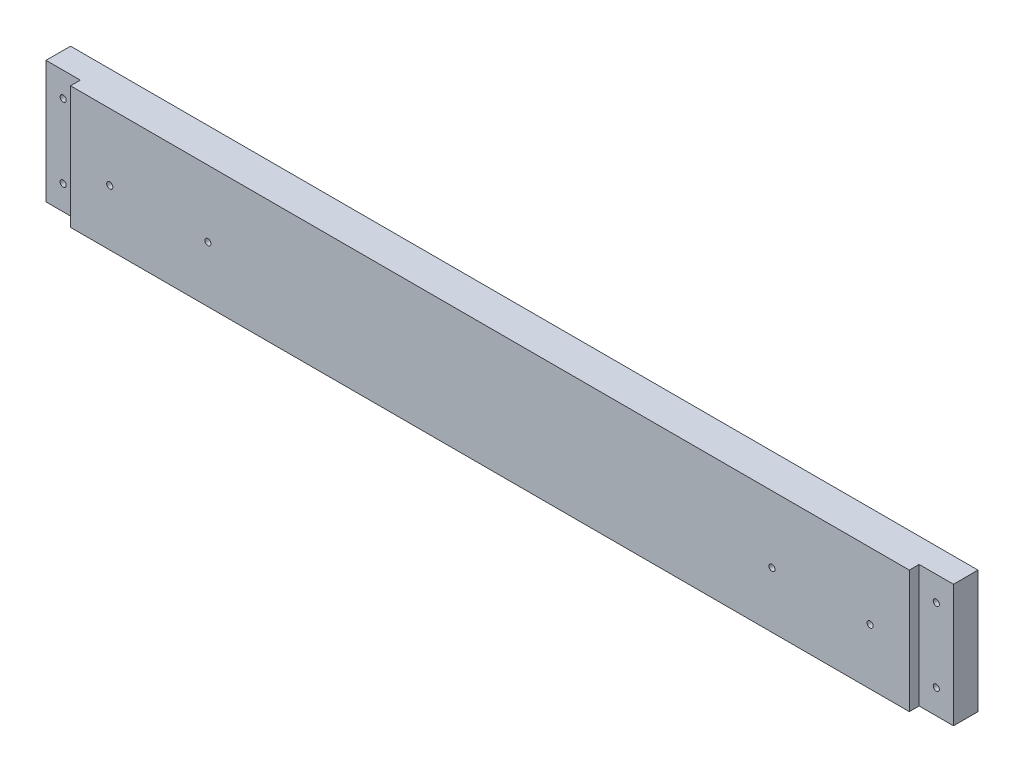
SolidWorks part; units mm, degrees
material "Pine"
ref_plane "Front Plane" through (0, 0, 0) normal (0, 0, 1) x (1, 0, 0)
ref_plane "Top Plane" through (0, 0, 0) normal (0, 1, 0) x (1, 0, 0)
ref_plane "Right Plane" through (0, 0, 0) normal (1, 0, 0) x (0, 0, -1)
sketch "Sketch1" plane through (0, 0, 0) normal (0, 0, 1) x (1, 0, 0)
  line L0 (8932.6508, -5243.5125) -> (10226.1458, -5243.5125)
  line L1 (9086.3208, -4722.0918) -> (10222.9708, -4853.7812)
  line L2 (8914.8708, -6342.0625) -> (10197.5708, -6342.0625)
  line L3 (8914.8708, -5808.6625) -> (10197.5708, -5808.6625)
  line L4 (8919.6333, -5253.0375) -> (10218.2083, -5253.0375)
  line L5 (9134.2633, -4656.1375) -> (9134.2633, -4638.3575)
  line L6 (9091.0833, -4638.3575) -> (9134.2633, -4638.3575)
  line L7 (9091.0833, -4567.2375) -> (9091.0833, -4638.3575)
  line L8 (9134.2633, -4656.1375) -> (9581.3033, -4656.1375)
  line L9 (9091.0833, -4567.2375) -> (9624.4833, -4567.2375)
  line L10 (9581.3033, -4656.1375) -> (9581.3033, -4638.3575)
  line L11 (9581.3033, -4638.3575) -> (9624.4833, -4638.3575)
  line L12 (9624.4833, -4567.2375) -> (9624.4833, -4638.3575)
  line L13 (8932.6508, -5225.7325) -> (9344.9775, -5225.7325)
  line L14 (8932.6508, -5256.2125) -> (8932.6508, -5243.5125)
  line L15 (8911.6958, -5256.2125) -> (8932.6508, -5256.2125)
  line L16 (8914.8708, -4722.0918) -> (9086.3208, -4722.0918)
  line L17 (8911.6958, -4715.5913) -> (8932.6508, -4715.5913)
  line L18 (8914.8708, -6342.0625) -> (8914.8708, -5808.6625)
  line L19 (12082.9917, -4722.0918) -> (10946.3417, -4853.7812)
  line L20 (12236.6617, -5243.5125) -> (10943.1667, -5243.5125)
  line L21 (10951.1042, -5253.0375) -> (12249.6792, -5253.0375)
  line L22 (10838.3917, -5656.2625) -> (11308.2917, -5656.2625)
  line L23 (10838.3917, -5719.7625) -> (11308.2917, -5719.7625)
  line L24 (10838.3917, -5742.5368) -> (11308.2917, -5742.5368)
  line L25 (10806.6417, -6342.0625) -> (11340.0417, -6342.0625)
  line L26 (10803.4667, -6335.7125) -> (11343.2167, -6335.7125)
  line L27 (10803.4667, -6317.9325) -> (11343.2167, -6317.9325)
  line L28 (10943.1667, -5225.7325) -> (11376.4483, -5225.7325)
  line L29 (11506.7292, -4754.5625) -> (10806.6417, -4827.5875)
  line L30 (11506.7292, -4567.2375) -> (11506.7292, -4754.5625)
  line L31 (10806.6417, -4567.2375) -> (10806.6417, -4827.5875)
  line L32 (10806.6417, -4567.2375) -> (11506.7292, -4567.2375)
  line L33 (10235.6708, -6329.3625) -> (10245.1958, -6329.3625)
  line L34 (10245.1958, -6329.3625) -> (10254.7208, -6278.5625)
  line L35 (10302.3458, -6329.3625) -> (10311.8708, -6278.5625)
  line L36 (10302.3458, -6329.3625) -> (10292.8208, -6329.3625)
  line L37 (10245.1958, -5821.3625) -> (10254.7208, -5872.1625)
  line L38 (10235.6708, -5821.3625) -> (10245.1958, -5821.3625)
  line L39 (10292.8208, -5821.3625) -> (10302.3458, -5821.3625)
  line L40 (10302.3458, -5821.3625) -> (10311.8708, -5872.1625)
  line L41 (10235.6708, -5821.3625) -> (10235.6708, -6329.3625)
  line L42 (10254.7208, -5872.1625) -> (10254.7208, -6278.5625)
  line L43 (10311.8708, -5872.1625) -> (10311.8708, -6278.5625)
  line L44 (10292.8208, -5821.3625) -> (10292.8208, -6329.3625)
  line L45 (8932.6508, -5225.7325) -> (8932.6508, -4715.5913)
  line L46 (8911.6958, -4715.5913) -> (8911.6958, -5256.2125)
  line L47 (8914.8708, -5248.275) -> (8914.8708, -4722.0918)
  line L48 (8919.6333, -5253.0375) -> (8914.8708, -5248.275)
  line L49 (8914.8708, -5145.0875) -> (8937.426, -5145.0875)
  line L50 (8914.8708, -5202.2375) -> (8937.426, -5202.2375)
  line L51 (10838.3917, -5656.2625) -> (10838.3917, -5719.7625)
  line L52 (10832.0417, -5736.1868) -> (10856.1717, -5736.1868)
  line L53 (10806.6417, -6342.0625) -> (10806.6417, -5818.7368)
  line L54 (10832.0417, -5649.9125) -> (10856.1717, -5649.9125)
  line L55 (10832.0417, -5726.1125) -> (10856.1717, -5726.1125)
  line L56 (10806.6417, -5818.7368) -> (10833.9015, -5818.7368)
  line L57 (10832.0417, -5806.0442) -> (10851.6815, -5806.0442)
  line L58 (10856.1717, -5801.5541) -> (10856.1717, -5736.1868)
  line L59 (10838.3917, -5814.2467) -> (10838.3917, -5742.5368)
  line L60 (10832.0417, -5806.0442) -> (10832.0417, -5736.1868)
  line L61 (10803.4667, -6317.9325) -> (10803.4667, -6335.7125)
  line L62 (10197.5708, -5808.6625) -> (10197.5708, -6342.0625)
  line L63 (9762.3842, -6348.4125) -> (9762.3842, -5802.3125)
  line L64 (9780.1642, -6348.4125) -> (9762.3842, -6348.4125)
  line L65 (9780.1642, -5802.3125) -> (9780.1642, -6348.4125)
  line L66 (9762.3842, -5802.3125) -> (9780.1642, -5802.3125)
  line L67 (9332.2775, -6348.4125) -> (9332.2775, -5802.3125)
  line L68 (9332.2775, -6348.4125) -> (9350.0575, -6348.4125)
  line L69 (9350.0575, -5802.3125) -> (9350.0575, -6348.4125)
  line L70 (9332.2775, -5802.3125) -> (9350.0575, -5802.3125)
  line L71 (9993.8374, -6061.075) -> (9993.8374, -6045.2418)
  line L72 (9998.5999, -6065.8375) -> (10014.4331, -6065.8375)
  line L73 (9998.5999, -6084.8875) -> (10014.4331, -6084.8875)
  line L74 (9993.8374, -6105.4832) -> (9993.8374, -6089.65)
  line L75 (9974.7874, -6105.4832) -> (9974.7874, -6089.65)
  line L76 (9954.1917, -6084.8875) -> (9970.0249, -6084.8875)
  line L77 (9974.7874, -6061.075) -> (9974.7874, -6045.2418)
  line L78 (9954.1917, -6065.8375) -> (9970.0249, -6065.8375)
  line L79 (10793.9417, -6237.2875) -> (10816.4969, -6237.2875)
  line L80 (10793.9417, -6294.4375) -> (10816.4969, -6294.4375)
  line L81 (10856.1717, -5649.9125) -> (10856.1717, -5726.1125)
  line L82 (10832.0417, -5726.1125) -> (10832.0417, -5649.9125)
  line L83 (10226.1458, -5225.7325) -> (10226.1458, -5243.5125)
  line L84 (10205.1908, -5257.8) -> (10205.1908, -4844.2499)
  line L85 (10230.9083, -4844.2499) -> (10230.9083, -5257.8)
  line L86 (10205.1908, -5257.8) -> (10230.9083, -5257.8)
  line L87 (10205.1908, -4844.2499) -> (10230.9083, -4844.2499)
  line L88 (10946.3417, -5176.8375) -> (10968.8969, -5176.8375)
  line L89 (9349.4676, -5141.9125) -> (9358.2674, -5141.9125)
  line L90 (10946.3417, -5119.6875) -> (10968.8969, -5119.6875)
  line L91 (9929.011, -4660.9635) -> (10066.0807, -4660.9635)
  line L92 (9929.011, -4678.7435) -> (10066.0807, -4678.7435)
  line L93 (10943.1667, -5225.7325) -> (10943.1667, -5243.5125)
  line L94 (10946.3417, -5248.275) -> (10951.1042, -5253.0375)
  line L95 (10946.3417, -5257.8063) -> (10946.3417, -4849.0188)
  line L96 (10964.1217, -5257.8) -> (10964.1217, -4844.2499)
  line L97 (10938.4042, -4844.2499) -> (10938.4042, -5257.8)
  line L98 (10938.4042, -5257.8) -> (10964.1217, -5257.8)
  line L99 (10964.1217, -4844.2499) -> (10938.4042, -4844.2499)
  line L100 (10344.8908, -4560.8875) -> (10369.0208, -4560.8875)
  line L101 (10344.8908, -4560.8875) -> (10369.0208, -4560.8875)
  line L102 (10800.2917, -4560.8875) -> (10824.4217, -4560.8875)
  line L103 (10200.4156, -5119.6875) -> (10222.9708, -5119.6875)
  line L104 (10200.4156, -5176.8375) -> (10222.9708, -5176.8375)
  line L105 (9344.9775, -5146.4026) -> (9344.9775, -5225.7325)
  line L106 (10344.8908, -4560.8875) -> (10344.8908, -4833.9375)
  line L107 (9792.8642, -5225.7325) -> (9792.8642, -5146.4026)
  line L108 (9362.7575, -5225.7325) -> (9775.0842, -5225.7325)
  line L109 (9680.3633, -4761.8396) -> (9680.3633, -4559.9604)
  line L110 (9656.2333, -4559.9604) -> (9680.3633, -4559.9604)
  line L111 (9656.2333, -4761.8396) -> (9680.3633, -4761.8396)
  line L112 (9656.2333, -4761.8396) -> (9656.2333, -4559.9604)
  line L113 (9779.5743, -5141.9125) -> (9788.374, -5141.9125)
  line L114 (10070.5708, -4665.4536) -> (10070.5708, -4674.2534)
  line L115 (9924.5208, -4674.2534) -> (9924.5208, -4665.4536)
  line L116 (12127.4417, -6188.3925) -> (12205.5015, -6188.3925)
  line L117 (12209.9917, -6170.6125) -> (12209.9917, -6183.9024)
  line L118 (9792.8642, -5225.7325) -> (10226.1458, -5225.7325)
  line L119 (9662.5833, -4754.5625) -> (10362.6708, -4827.5875)
  line L120 (9662.5833, -4567.2375) -> (9662.5833, -4754.5625)
  line L121 (10362.6708, -4567.2375) -> (10362.6708, -4827.5875)
  line L122 (9662.5833, -4567.2375) -> (10362.6708, -4567.2375)
  line L123 (10824.4217, -4833.9375) -> (10800.2917, -4833.9375)
  line L124 (10800.2917, -4833.9375) -> (10800.2917, -4560.8875)
  line L125 (10824.4217, -4560.8875) -> (10824.4217, -4833.9375)
  line L126 (10344.8908, -4833.9375) -> (10369.0208, -4833.9375)
  line L127 (10369.0208, -4833.9375) -> (10369.0208, -4560.8875)
  line L128 (10222.9708, -5248.275) -> (10218.2083, -5253.0375)
  line L129 (10222.9708, -5257.8063) -> (10222.9708, -4849.0188)
  line L130 (11734.6544, -5701.375) -> (11739.2301, -5701.375)
  line L131 (9362.7575, -5225.7325) -> (9362.7575, -5146.4026)
  line L132 (9775.0842, -5146.4026) -> (9775.0842, -5225.7325)
  line L133 (11761.3864, -5701.375) -> (11756.8282, -5701.375)
  line L134 (11734.6544, -5693.755) -> (11739.2301, -5693.755)
  line L135 (11761.4039, -5693.755) -> (11756.8282, -5693.755)
  line L136 (11734.6544, -5701.375) -> (11739.2301, -5701.375)
  line L137 (11744.3462, -5721.3024) -> (11744.3462, -5706.4179)
  line L138 (11751.7122, -5721.3024) -> (11751.7122, -5706.4179)
  line L139 (11740.0917, -6170.6125) -> (11740.0917, -6183.9024)
  line L140 (11689.2917, -6188.3925) -> (11822.6417, -6188.3925)
  line L141 (11689.2917, -6348.4093) -> (11689.2917, -6164.2657)
  line L142 (11689.2917, -6164.2657) -> (11746.4417, -6164.2657)
  line L143 (11746.4417, -6164.2657) -> (11746.4417, -6188.3925)
  line L144 (11689.2917, -6164.2657) -> (11746.4417, -6164.2657)
  line L145 (11340.0417, -5818.7368) -> (11340.0417, -6342.0625)
  line L146 (11290.5117, -5726.1125) -> (11314.6417, -5726.1125)
  line L147 (11290.5117, -5649.9125) -> (11290.5117, -5726.1125)
  line L148 (11340.0417, -5818.7368) -> (11312.7818, -5818.7368)
  line L149 (11314.6417, -5806.0442) -> (11295.0018, -5806.0442)
  line L150 (11290.5117, -5801.5541) -> (11290.5117, -5736.1868)
  line L151 (11308.2917, -5814.2467) -> (11308.2917, -5742.5368)
  line L152 (11314.6417, -5806.0442) -> (11314.6417, -5736.1868)
  line L153 (11290.5117, -5736.1868) -> (11314.6417, -5736.1868)
  line L154 (11848.0417, -6267.1325) -> (11962.3417, -6267.1325)
  line L155 (11962.3417, -6267.1325) -> (11962.3417, -6203.6325)
  line L156 (11343.2167, -6317.9325) -> (11343.2167, -6335.7125)
  line L157 (11365.4417, -5656.2625) -> (11365.4417, -5719.7625)
  line L158 (11365.4417, -5656.2625) -> (11479.7417, -5656.2625)
  line L159 (11778.1917, -6071.3937) -> (11802.3217, -6071.3937)
  line L160 (11314.6417, -5726.1125) -> (11314.6417, -5649.9125)
  line L161 (11314.6417, -5649.9125) -> (11290.5117, -5649.9125)
  line L162 (11308.2917, -5719.7625) -> (11308.2917, -5656.2625)
  line L163 (11689.2917, -6348.4093) -> (11713.4217, -6348.4093)
  line L164 (12203.6417, -6164.2657) -> (12260.7917, -6164.2657)
  line L165 (11713.4217, -6348.4093) -> (11713.4217, -6164.2657)
  line L166 (11695.6417, -6342.0625) -> (11695.6417, -6170.6125)
  line L167 (11695.6417, -6048.5337) -> (11699.4517, -6052.3437)
  line L168 (11822.6417, -6292.5325) -> (11822.6417, -6188.3925)
  line L169 (11695.6417, -6342.0625) -> (11695.6417, -6170.6125)
  line L170 (11848.0417, -6203.6325) -> (11962.3417, -6203.6325)
  line L171 (11848.0417, -6203.6325) -> (11848.0417, -6267.1325)
  line L172 (11987.7417, -6267.1325) -> (11987.7417, -6203.6325)
  line L173 (11784.5417, -6077.7437) -> (11784.5417, -6141.2438)
  line L174 (11517.8417, -5656.2625) -> (11632.1417, -5656.2625)
  line L175 (11632.1417, -5656.2625) -> (11632.1417, -5719.7625)
  line L176 (11632.1417, -5719.7625) -> (11517.8417, -5719.7625)
  line L177 (11517.8417, -5719.7625) -> (11517.8417, -5656.2625)
  line L178 (11692.4667, -6028.2137) -> (11692.4667, -6045.9937)
  line L179 (11695.6417, -5979.3188) -> (11718.1969, -5979.3188)
  line L180 (11695.6417, -5922.1687) -> (11718.1969, -5922.1687)
  line L181 (11821.0415, -5722.9375) -> (11821.0415, -5943.6)
  line L182 (11687.7042, -5651.5) -> (11701.9917, -5651.5)
  line L183 (11687.7042, -5651.5) -> (11687.7042, -6055.5251)
  line L184 (11687.7042, -6055.5251) -> (11701.9917, -6055.5251)
  line L185 (11701.9917, -6055.5251) -> (11701.9917, -5651.5)
  line L186 (11695.6417, -6055.2013) -> (11695.6417, -5649.595)
  line L187 (11695.6417, -5656.2625) -> (11695.6417, -6048.5337)
  line L188 (11695.6417, -6170.6125) -> (11740.0917, -6170.6125)
  line L189 (12203.6417, -6164.2657) -> (12203.6417, -6188.3925)
  line L190 (12254.4417, -6342.0625) -> (12254.4417, -6170.6125)
  line L191 (12129.0419, -5943.6) -> (12129.0419, -5722.9375)
  line L192 (12254.4417, -6048.5337) -> (12250.6317, -6052.3437)
  line L193 (12257.6167, -6045.9937) -> (12257.6167, -6028.2137)
  line L194 (12248.0917, -5651.5) -> (12262.3792, -5651.5)
  line L195 (12262.3792, -5651.5) -> (12262.3792, -6055.5251)
  line L196 (12262.3792, -6055.5251) -> (12248.0917, -6055.5251)
  line L197 (12248.0917, -6055.5251) -> (12248.0917, -5651.5)
  line L198 (12254.4417, -6141.2438) -> (12254.4417, -6077.7437)
  line L199 (12236.6617, -6164.2657) -> (12260.7917, -6164.2657)
  line L200 (12102.0417, -6267.1325) -> (11987.7417, -6267.1325)
  line L201 (11330.1865, -6237.2875) -> (11352.7417, -6237.2875)
  line L202 (11330.1865, -6294.4375) -> (11352.7417, -6294.4375)
  line L203 (11474.6617, -5851.8425) -> (11492.4417, -5851.8425)
  line L204 (11474.6617, -5808.6625) -> (11474.6617, -5851.8425)
  line L205 (11403.5417, -5808.6625) -> (11474.6617, -5808.6625)
  line L206 (11492.4417, -5851.8425) -> (11492.4417, -6298.8825)
  line L207 (11403.5417, -6342.0625) -> (11403.5417, -5808.6625)
  line L208 (11474.6617, -6298.8825) -> (11492.4417, -6298.8825)
  line L209 (11474.6617, -6342.0625) -> (11474.6617, -6298.8825)
  line L210 (11403.5417, -6342.0625) -> (11474.6617, -6342.0625)
  line L211 (11619.4417, -5851.8425) -> (11601.6617, -5851.8425)
  line L212 (11601.6617, -5808.6625) -> (11601.6617, -5851.8425)
  line L213 (11530.5417, -5808.6625) -> (11601.6617, -5808.6625)
  line L214 (11619.4417, -5851.8425) -> (11619.4417, -6298.8825)
  line L215 (11530.5417, -6342.0625) -> (11530.5417, -5808.6625)
  line L216 (11619.4417, -6298.8825) -> (11601.6617, -6298.8825)
  line L217 (11601.6617, -6342.0625) -> (11601.6617, -6298.8825)
  line L218 (11530.5417, -6342.0625) -> (11601.6617, -6342.0625)
  line L219 (11479.7417, -5719.7625) -> (11479.7417, -5656.2625)
  line L220 (11365.4417, -5719.7625) -> (11479.7417, -5719.7625)
  line L221 (11778.1917, -6147.5937) -> (11802.3217, -6147.5937)
  line L222 (11802.3217, -6071.3937) -> (11802.3217, -6147.5937)
  line L223 (11778.1917, -6147.5937) -> (11778.1917, -6071.3937)
  line L224 (12254.4417, -5922.1687) -> (12231.8865, -5922.1687)
  line L225 (12254.4417, -5979.3188) -> (12231.8865, -5979.3188)
  line L226 (12254.4417, -6055.2013) -> (12254.4417, -5649.595)
  line L227 (12254.4417, -6048.5337) -> (12254.4417, -5656.2625)
  line L228 (11841.6917, -5702.2873) -> (12108.3917, -5702.2873)
  line L229 (11822.6417, -6292.5325) -> (12127.4417, -6292.5325)
  line L230 (12127.4417, -6292.5325) -> (12127.4417, -6188.3925)
  line L231 (12254.4417, -6170.6125) -> (12209.9917, -6170.6125)
  line L232 (11695.6417, -6342.0625) -> (12254.4417, -6342.0625)
  line L233 (12236.6617, -6348.4093) -> (12260.7917, -6348.4093)
  line L234 (12260.7917, -6348.4093) -> (12260.7917, -6164.2657)
  line L235 (12236.6617, -6348.4093) -> (12236.6617, -6164.2657)
  line L236 (12102.0417, -6203.6325) -> (12102.0417, -6267.1325)
  line L237 (11987.7417, -6203.6325) -> (12102.0417, -6203.6325)
  line L238 (12236.6617, -6147.5937) -> (12236.6617, -6071.3937)
  line L239 (12203.6417, -6188.3925) -> (12260.7917, -6188.3925)
  line L240 (11098.7417, -4665.4536) -> (11098.7417, -4674.2534)
  line L241 (11394.2283, -5146.4026) -> (11394.2283, -5225.7325)
  line L242 (11376.4483, -5225.7325) -> (11376.4483, -5146.4026)
  line L243 (11394.2283, -5225.7325) -> (11806.555, -5225.7325)
  line L244 (11841.6917, -5964.2502) -> (12108.3917, -5964.2502)
  line L245 (12236.6617, -6147.5937) -> (12260.7917, -6147.5937)
  line L246 (12236.6617, -5256.2125) -> (12236.6617, -5243.5125)
  line L247 (12260.7917, -6147.5937) -> (12260.7917, -6071.3937)
  line L248 (12260.7917, -6071.3937) -> (12236.6617, -6071.3937)
  line L249 (12254.4417, -6077.7437) -> (11784.5417, -6077.7437)
  line L250 (11784.5417, -6141.2438) -> (12254.4417, -6141.2438)
  line L252 (12254.4417, -5656.2625) -> (11695.6417, -5656.2625)
  line L253 (11699.4517, -6052.3437) -> (12250.6317, -6052.3437)
  line L254 (11692.4667, -6045.9937) -> (12257.6167, -6045.9937)
  line L255 (11692.4667, -6028.2137) -> (12257.6167, -6028.2137)
  line L256 (11824.335, -5146.4026) -> (11824.335, -5225.7325)
  line L257 (11811.0451, -5141.9125) -> (11819.8449, -5141.9125)
  line L258 (11244.7917, -4674.2534) -> (11244.7917, -4665.4536)
  line L259 (11806.555, -5225.7325) -> (11806.555, -5146.4026)
  line L260 (11488.9492, -4761.8396) -> (11488.9492, -4559.9604)
  line L261 (11488.9492, -4559.9604) -> (11513.0792, -4559.9604)
  line L262 (11488.9492, -4761.8396) -> (11513.0792, -4761.8396)
  line L263 (11513.0792, -4761.8396) -> (11513.0792, -4559.9604)
  line L264 (11240.3015, -4660.9635) -> (11103.2318, -4660.9635)
  line L265 (11103.2318, -4678.7435) -> (11240.3015, -4678.7435)
  line L266 (12236.6617, -5225.7325) -> (12236.6617, -4715.5913)
  line L267 (12257.6167, -4715.5913) -> (12257.6167, -5256.2125)
  line L268 (12254.4417, -5248.275) -> (12254.4417, -4722.0918)
  line L269 (12236.6617, -5225.7325) -> (11824.335, -5225.7325)
  line L270 (12035.0492, -4656.1375) -> (12035.0492, -4638.3575)
  line L271 (12078.2292, -4638.3575) -> (12035.0492, -4638.3575)
  line L272 (12078.2292, -4567.2375) -> (12078.2292, -4638.3575)
  line L273 (12035.0492, -4656.1375) -> (11588.0092, -4656.1375)
  line L274 (11544.8292, -4567.2375) -> (12078.2292, -4567.2375)
  line L275 (11588.0092, -4656.1375) -> (11588.0092, -4638.3575)
  line L276 (11544.8292, -4638.3575) -> (11588.0092, -4638.3575)
  line L277 (11544.8292, -4567.2375) -> (11544.8292, -4638.3575)
  line L278 (12249.6792, -5253.0375) -> (12254.4417, -5248.275)
  line L280 (12257.6167, -5256.2125) -> (12236.6617, -5256.2125)
  line L281 (12231.8865, -5145.0875) -> (12254.4417, -5145.0875)
  line L282 (12231.8865, -5202.2375) -> (12254.4417, -5202.2375)
  line L283 (12236.6617, -4715.5913) -> (12257.6167, -4715.5913)
  line L284 (12082.9917, -4722.0918) -> (12254.4417, -4722.0918)
  line L285 (11380.9385, -5141.9125) -> (11389.7382, -5141.9125)
  circle A0 centre (8923.7608, -4778.9042) radius 1.5875
  circle A1 centre (9062.6598, -4736.3765) radius 2.3685
  circle A2 centre (9051.3958, -6281.7375) radius 22.225
  circle A3 centre (9083.1458, -6249.9875) radius 1.5875
  circle A4 centre (9083.1458, -6313.4875) radius 1.5875
  circle A5 centre (9019.6458, -6249.9875) radius 1.5875
  circle A6 centre (9019.6458, -6313.4875) radius 1.5875
  circle A7 centre (8972.3383, -5202.2375) radius 1.5875
  circle A8 centre (8923.7608, -5015.9708) radius 1.5875
  circle A9 centre (8923.7608, -5134.5042) radius 1.5875
  circle A10 centre (9054.5708, -5234.6225) radius 1.5875
  circle A11 centre (8923.7608, -4897.4375) radius 1.5875
  circle A12 centre (8972.3383, -5087.9375) radius 1.5875
  circle A13 centre (8972.3383, -5145.0875) radius 1.5875
  circle A14 centre (10847.2817, -5668.9625) radius 1.5875
  circle A15 centre (10847.2817, -5707.0625) radius 1.5875
  circle A16 centre (10847.2817, -5755.2368) radius 1.5875
  circle A17 centre (10851.4092, -6237.2875) radius 1.5875
  circle A18 centre (10851.4092, -6294.4375) radius 1.5875
  circle A19 centre (10847.2817, -5793.3442) radius 1.5875
  arc A20 (10833.9015, -5818.7368) -> (10838.3917, -5814.2467) centre (10836.1466, -5816.4918) ccw
  arc A21 (10851.6815, -5806.0442) -> (10856.1717, -5801.5541) centre (10853.9266, -5803.7992) ccw
  circle A22 centre (10882.8417, -6040.4375) radius 1.5875
  circle A23 centre (10882.8417, -6218.2375) radius 1.5875
  circle A24 centre (10882.8417, -5862.6375) radius 1.5875
  circle A25 centre (10908.2417, -6326.8225) radius 1.5875
  circle A26 centre (10908.2417, -6326.8225) radius 1.5875
  circle A27 centre (10851.4092, -6180.1375) radius 1.5875
  circle A28 centre (10815.5317, -4783.4231) radius 1.5875
  circle A29 centre (10815.5317, -4696.9488) radius 1.5875
  circle A30 centre (10815.5317, -4610.4746) radius 1.5875
  circle A31 centre (10979.1323, -4867.0082) radius 2.3685
  circle A32 centre (10190.1802, -4867.0082) radius 2.3685
  circle A33 centre (10955.2317, -4929.9812) radius 1.5875
  circle A34 centre (10955.2317, -5031.5812) radius 1.5875
  circle A35 centre (10214.0808, -4929.9812) radius 1.5875
  circle A36 centre (10214.0808, -5031.5812) radius 1.5875
  circle A37 centre (9341.1675, -6265.8625) radius 1.5875
  circle A38 centre (9771.2742, -5884.8625) radius 1.5875
  circle A39 centre (9771.2742, -6138.8625) radius 1.5875
  circle A40 centre (9771.2742, -6011.8625) radius 1.5875
  arc A41 (10036.2287, -6113.8083) -> (10051.3426, -6111.6033) centre (10042.9639, -6107.0732) ccw
  arc A42 (10051.3426, -6111.6033) -> (10051.3426, -6039.1217) centre (9984.3124, -6075.3625) ccw
  arc A43 (10051.3426, -6039.1217) -> (10036.2287, -6036.9167) centre (10042.9639, -6043.6518) ccw
  arc A44 (10034.5851, -6102.5431) -> (10034.5851, -6048.1819) centre (9984.3124, -6075.3625) ccw
  arc A45 (10034.5851, -6102.5431) -> (10036.2287, -6113.8083) centre (10042.9639, -6107.0732) ccw
  arc A46 (10036.2287, -6036.9167) -> (10034.5851, -6048.1819) centre (10042.9639, -6043.6518) ccw
  arc A47 (9945.8666, -6127.2787) -> (9948.0717, -6142.3927) centre (9952.6018, -6134.0139) ccw
  arc A48 (9948.0717, -6142.3927) -> (10020.5532, -6142.3927) centre (9984.3124, -6075.3625) ccw
  arc A49 (10020.5532, -6142.3927) -> (10022.7583, -6127.2787) centre (10016.0231, -6134.0139) ccw
  arc A50 (9957.1319, -6125.6352) -> (10011.493, -6125.6352) centre (9984.3124, -6075.3625) ccw
  arc A51 (9957.1319, -6125.6352) -> (9945.8666, -6127.2787) centre (9952.6018, -6134.0139) ccw
  arc A52 (10022.7583, -6127.2787) -> (10011.493, -6125.6352) centre (10016.0231, -6134.0139) ccw
  arc A53 (9932.3962, -6036.9167) -> (9917.2822, -6039.1217) centre (9925.661, -6043.6518) ccw
  arc A54 (9917.2822, -6039.1217) -> (9917.2822, -6111.6033) centre (9984.3124, -6075.3625) ccw
  arc A55 (9917.2822, -6111.6033) -> (9932.3962, -6113.8083) centre (9925.661, -6107.0732) ccw
  arc A56 (9934.0398, -6048.1819) -> (9934.0398, -6102.5431) centre (9984.3124, -6075.3625) ccw
  arc A57 (9934.0398, -6048.1819) -> (9932.3962, -6036.9167) centre (9925.661, -6043.6518) ccw
  arc A58 (9932.3962, -6113.8083) -> (9934.0398, -6102.5431) centre (9925.661, -6107.0732) ccw
  arc A59 (9945.8666, -6023.4463) -> (9957.1319, -6025.0898) centre (9952.6018, -6016.7111) ccw
  arc A60 (10011.493, -6025.0898) -> (10022.7583, -6023.4463) centre (10016.0231, -6016.7111) ccw
  arc A61 (10011.493, -6025.0898) -> (9957.1319, -6025.0898) centre (9984.3124, -6075.3625) ccw
  arc A62 (9948.0717, -6008.3323) -> (9945.8666, -6023.4463) centre (9952.6018, -6016.7111) ccw
  arc A63 (10020.5532, -6008.3323) -> (9948.0717, -6008.3323) centre (9984.3124, -6075.3625) ccw
  arc A64 (10022.7583, -6023.4463) -> (10020.5532, -6008.3323) centre (10016.0231, -6016.7111) ccw
  arc A65 (10005.0943, -6187.7574) -> (10096.7073, -6096.1443) centre (9984.3124, -6075.3625) ccw
  arc A66 (9993.8374, -6178.3911) -> (10005.0943, -6187.7574) centre (10003.3624, -6178.3911) ccw
  arc A67 (10001.6306, -6169.0249) -> (10077.9748, -6092.6807) centre (9984.3124, -6075.3625) ccw
  arc A68 (10087.3411, -6084.8875) -> (10077.9748, -6092.6807) centre (10087.3411, -6094.4125) ccw
  arc A69 (10001.6306, -6169.0249) -> (9993.8374, -6178.3911) centre (10003.3624, -6178.3911) ccw
  arc A70 (9963.5306, -6187.7574) -> (9974.7874, -6178.3911) centre (9965.2624, -6178.3911) ccw
  arc A71 (9871.9176, -6096.1443) -> (9963.5306, -6187.7574) centre (9984.3124, -6075.3625) ccw
  arc A72 (9881.2838, -6084.8875) -> (9871.9176, -6096.1443) centre (9881.2838, -6094.4125) ccw
  arc A73 (9890.65, -6092.6807) -> (9966.9943, -6169.0249) centre (9984.3124, -6075.3625) ccw
  arc A74 (9974.7874, -6178.3911) -> (9966.9943, -6169.0249) centre (9965.2624, -6178.3911) ccw
  arc A75 (9890.65, -6092.6807) -> (9881.2838, -6084.8875) centre (9881.2838, -6094.4125) ccw
  arc A76 (9871.9176, -6054.5807) -> (9881.2838, -6065.8375) centre (9881.2838, -6056.3125) ccw
  arc A77 (9963.5306, -5962.9676) -> (9871.9176, -6054.5807) centre (9984.3124, -6075.3625) ccw
  arc A78 (9974.7874, -5972.3339) -> (9963.5306, -5962.9676) centre (9965.2624, -5972.3339) ccw
  arc A79 (9966.9943, -5981.7001) -> (9890.65, -6058.0443) centre (9984.3124, -6075.3625) ccw
  arc A80 (9881.2838, -6065.8375) -> (9890.65, -6058.0443) centre (9881.2838, -6056.3125) ccw
  arc A81 (9966.9943, -5981.7001) -> (9974.7874, -5972.3339) centre (9965.2624, -5972.3339) ccw
  arc A82 (10077.9748, -6058.0443) -> (10087.3411, -6065.8375) centre (10087.3411, -6056.3125) ccw
  arc A83 (9993.8374, -5972.3339) -> (10001.6306, -5981.7001) centre (10003.3624, -5972.3339) ccw
  arc A84 (10077.9748, -6058.0443) -> (10001.6306, -5981.7001) centre (9984.3124, -6075.3625) ccw
  arc A85 (10087.3411, -6065.8375) -> (10096.7073, -6054.5807) centre (10087.3411, -6056.3125) ccw
  arc A86 (10096.7073, -6054.5807) -> (10005.0943, -5962.9676) centre (9984.3124, -6075.3625) ccw
  arc A87 (10005.0943, -5962.9676) -> (9993.8374, -5972.3339) centre (10003.3624, -5972.3339) ccw
  arc A88 (10014.4331, -6065.8375) -> (10018.7361, -6059.0339) centre (10014.4331, -6061.075) ccw
  arc A89 (10018.7361, -6059.0339) -> (10000.641, -6040.9388) centre (9984.3124, -6075.3625) ccw
  arc A90 (10000.641, -6040.9388) -> (9993.8374, -6045.2418) centre (9998.5999, -6045.2418) ccw
  arc A91 (9993.8374, -6061.075) -> (9998.5999, -6065.8375) centre (9998.5999, -6061.075) ccw
  arc A92 (9993.8374, -6105.4832) -> (10000.641, -6109.7862) centre (9998.5999, -6105.4832) ccw
  arc A93 (10000.641, -6109.7862) -> (10018.7361, -6091.6911) centre (9984.3124, -6075.3625) ccw
  arc A94 (10018.7361, -6091.6911) -> (10014.4331, -6084.8875) centre (10014.4331, -6089.65) ccw
  arc A95 (9998.5999, -6084.8875) -> (9993.8374, -6089.65) centre (9998.5999, -6089.65) ccw
  arc A96 (9954.1917, -6084.8875) -> (9949.8888, -6091.6911) centre (9954.1917, -6089.65) ccw
  arc A97 (9949.8888, -6091.6911) -> (9967.9839, -6109.7862) centre (9984.3124, -6075.3625) ccw
  arc A98 (9967.9839, -6109.7862) -> (9974.7874, -6105.4832) centre (9970.0249, -6105.4832) ccw
  arc A99 (9974.7874, -6089.65) -> (9970.0249, -6084.8875) centre (9970.0249, -6089.65) ccw
  arc A100 (9970.0249, -6065.8375) -> (9974.7874, -6061.075) centre (9970.0249, -6061.075) ccw
  arc A101 (9949.8888, -6059.0339) -> (9954.1917, -6065.8375) centre (9954.1917, -6061.075) ccw
  arc A102 (9967.9839, -6040.9388) -> (9949.8888, -6059.0339) centre (9984.3124, -6075.3625) ccw
  arc A103 (9974.7874, -6045.2418) -> (9967.9839, -6040.9388) centre (9970.0249, -6045.2418) ccw
  arc A104 (10096.7073, -6096.1443) -> (10087.3411, -6084.8875) centre (10087.3411, -6094.4125) ccw
  circle A105 centre (9771.2742, -6265.8625) radius 1.5875
  circle A106 centre (9341.1675, -5884.8625) radius 1.5875
  circle A107 centre (9341.1675, -6138.8625) radius 1.5875
  circle A108 centre (9341.1675, -6011.8625) radius 1.5875
  circle A109 centre (11037.2315, -4887.5494) radius 15.0812
  arc A110 (9349.4676, -5141.9125) -> (9344.9775, -5146.4026) centre (9347.2226, -5144.1576) ccw
  arc A111 (9362.7575, -5146.4026) -> (9358.2674, -5141.9125) centre (9360.5124, -5144.1576) ccw
  circle A112 centre (9946.7458, -4669.8535) radius 1.5875
  arc A113 (9924.5208, -4674.2534) -> (9929.011, -4678.7435) centre (9926.7659, -4676.4984) ccw
  circle A114 centre (11003.8092, -5176.8375) radius 1.5875
  circle A115 centre (11003.8092, -5119.6875) radius 1.5875
  circle A116 centre (10353.7808, -4696.9488) radius 1.5875
  circle A117 centre (10353.7808, -4610.4746) radius 1.5875
  circle A118 centre (10353.7808, -4783.4231) radius 1.5875
  circle A119 centre (11003.8092, -5062.5375) radius 1.5875
  circle A120 centre (9353.8675, -5160.9625) radius 1.5875
  circle A121 centre (9638.7708, -5234.6225) radius 1.5875
  circle A122 centre (9671.4733, -4724.1144) radius 1.5875
  circle A123 centre (9671.4733, -4661.3637) radius 1.5875
  circle A124 centre (9671.4733, -4598.6129) radius 1.5875
  arc A125 (9792.8642, -5146.4026) -> (9788.374, -5141.9125) centre (9790.6191, -5144.1576) ccw
  arc A126 (9779.5743, -5141.9125) -> (9775.0842, -5146.4026) centre (9777.3292, -5144.1576) ccw
  circle A127 centre (10048.3458, -4669.8535) radius 1.5875
  arc A128 (10070.5708, -4665.4536) -> (10066.0807, -4660.9635) centre (10068.3258, -4663.2086) ccw
  arc A129 (10066.0807, -4678.7435) -> (10070.5708, -4674.2534) centre (10068.3258, -4676.4984) ccw
  circle A130 centre (9997.5458, -4669.8535) radius 1.5875
  arc A131 (9929.011, -4660.9635) -> (9924.5208, -4665.4536) centre (9926.7659, -4663.2086) ccw
  circle A132 centre (10132.081, -4887.5494) radius 15.0812
  circle A133 centre (10165.5033, -5176.8375) radius 1.5875
  circle A134 centre (10165.5033, -5119.6875) radius 1.5875
  circle A135 centre (9486.3708, -5234.6225) radius 1.5875
  circle A136 centre (10165.5033, -5062.5375) radius 1.5875
  circle A137 centre (9206.9708, -5234.6225) radius 1.5875
  circle A138 centre (10070.5708, -5234.6225) radius 1.5875
  circle A139 centre (9918.1708, -5234.6225) radius 1.5875
  circle A140 centre (9783.9742, -5160.9625) radius 1.5875
  circle A141 centre (9783.9742, -5193.9825) radius 1.5875
  circle A142 centre (9353.8675, -5193.9825) radius 1.5875
  circle A143 centre (11073.3417, -6326.8225) radius 1.5875
  circle A144 centre (11073.3417, -6326.8225) radius 1.5875
  circle A145 centre (11295.2742, -6180.1375) radius 1.5875
  circle A146 centre (11295.2742, -6294.4375) radius 1.5875
  circle A147 centre (11295.2742, -6237.2875) radius 1.5875
  circle A148 centre (11975.0417, -5692.775) radius 3.4925
  circle A149 centre (11263.8417, -5862.6375) radius 1.5875
  arc A150 (11739.2301, -5701.375) -> (11744.3462, -5706.4179) centre (11748.0292, -5697.565) ccw
  arc A151 (11751.7122, -5706.4179) -> (11756.8282, -5701.375) centre (11748.0292, -5697.565) ccw
  arc A152 (11744.3462, -5721.3024) -> (11751.7122, -5721.3024) centre (11748.0292, -5725.505) ccw
  arc A153 (11734.6544, -5693.755) -> (11724.9787, -5697.565) centre (11730.5667, -5697.565) ccw
  arc A154 (11756.8282, -5693.755) -> (11739.2301, -5693.755) centre (11748.0292, -5697.565) ccw
  arc A155 (11724.9787, -5697.565) -> (11734.6544, -5701.375) centre (11730.5667, -5697.565) ccw
  arc A156 (11761.3864, -5701.375) -> (11771.0797, -5697.565) centre (11765.4842, -5697.565) ccw
  arc A157 (11771.0797, -5697.565) -> (11761.4039, -5693.755) centre (11765.4917, -5697.565) ccw
  arc A158 (11740.0917, -6183.9024) -> (11744.5818, -6188.3925) centre (11742.3367, -6186.1474) ccw
  arc A159 (12205.5015, -6188.3925) -> (12209.9917, -6183.9024) centre (12207.7466, -6186.1474) ccw
  circle A160 centre (11299.4017, -5793.3442) radius 1.5875
  arc A161 (11308.2917, -5814.2467) -> (11312.7818, -5818.7368) centre (11310.5367, -5816.4918) ccw
  arc A162 (11290.5117, -5801.5541) -> (11295.0018, -5806.0442) centre (11292.7567, -5803.7992) ccw
  circle A163 centre (11704.5317, -6314.149) radius 1.5875
  circle A164 centre (11748.9817, -6208.7125) radius 1.5875
  circle A165 centre (11263.8417, -6218.2375) radius 1.5875
  circle A166 centre (11263.8417, -6040.4375) radius 1.5875
  circle A167 centre (11238.4417, -6326.8225) radius 1.5875
  circle A168 centre (11238.4417, -6326.8225) radius 1.5875
  circle A169 centre (11299.4017, -5668.9625) radius 1.5875
  circle A170 centre (11299.4017, -5707.0625) radius 1.5875
  circle A171 centre (11726.7567, -6179.5025) radius 1.5875
  circle A172 centre (11704.5317, -6199.3198) radius 1.5875
  circle A173 centre (11748.9817, -6272.2125) radius 1.5875
  circle A174 centre (11704.5317, -6256.7344) radius 1.5875
  circle A175 centre (11299.4017, -5755.2368) radius 1.5875
  circle A176 centre (11913.4467, -6301.4225) radius 1.5875
  circle A177 centre (11790.2567, -6301.4225) radius 1.5875
  circle A178 centre (11793.4317, -6128.5437) radius 1.5875
  circle A179 centre (11753.1092, -5865.0188) radius 1.5875
  circle A180 centre (11809.9417, -6037.1038) radius 1.5875
  circle A181 centre (11809.9417, -6037.1038) radius 1.5875
  circle A182 centre (11753.1092, -5922.1687) radius 1.5875
  circle A183 centre (11975.0417, -5973.7625) radius 3.4925
  circle A184 centre (11975.0417, -6037.1038) radius 1.5875
  circle A185 centre (11753.1092, -5979.3188) radius 1.5875
  circle A186 centre (11975.0417, -6037.1038) radius 1.5875
  arc A187 (11841.6917, -5702.2873) -> (11821.0415, -5722.9375) centre (11841.6917, -5722.9375) ccw
  circle A188 centre (11811.5292, -5833.2687) radius 3.4925
  arc A189 (11821.0415, -5943.6) -> (11841.6917, -5964.2502) centre (11841.6917, -5943.6) ccw
  circle A190 centre (12196.9742, -5865.0188) radius 1.5875
  arc A191 (12129.0419, -5722.9375) -> (12108.3917, -5702.2873) centre (12108.3917, -5722.9375) ccw
  circle A192 centre (12036.6367, -6301.4225) radius 1.5875
  circle A193 centre (12159.8267, -6301.4225) radius 1.5875
  circle A194 centre (12138.5542, -5833.2687) radius 3.4925
  circle A195 centre (12197.2917, -5761.0375) radius 15.0812
  circle A196 centre (11793.4317, -6090.4437) radius 1.5875
  circle A197 centre (12196.9742, -5922.1687) radius 1.5875
  arc A198 (12108.3917, -5964.2502) -> (12129.0419, -5943.6) centre (12108.3917, -5943.6) ccw
  circle A199 centre (12196.9742, -5979.3188) radius 1.5875
  circle A200 centre (12201.1017, -6272.2125) radius 1.5875
  circle A201 centre (12245.5517, -6314.149) radius 1.5875
  circle A202 centre (12245.5517, -6256.7344) radius 1.5875
  circle A203 centre (12201.1017, -6208.7125) radius 1.5875
  circle A204 centre (12223.3267, -6179.5025) radius 1.5875
  circle A205 centre (12245.5517, -6199.3198) radius 1.5875
  circle A206 centre (11171.7667, -4669.8535) radius 1.5875
  circle A207 centre (11222.5667, -4669.8535) radius 1.5875
  arc A208 (11240.3015, -4678.7435) -> (11244.7917, -4674.2534) centre (11242.5466, -4676.4984) ccw
  circle A209 centre (11385.3383, -5193.9825) radius 1.5875
  circle A210 centre (12106.6527, -4736.3765) radius 2.3685
  circle A211 centre (12140.1417, -6037.1038) radius 1.5875
  circle A212 centre (12140.1417, -6037.1038) radius 1.5875
  circle A213 centre (12245.5517, -6090.4437) radius 1.5875
  circle A214 centre (12245.5517, -6128.5437) radius 1.5875
  circle A215 centre (11385.3383, -5160.9625) radius 1.5875
  arc A216 (11824.335, -5146.4026) -> (11819.8449, -5141.9125) centre (11822.0899, -5144.1576) ccw
  arc A217 (11811.0451, -5141.9125) -> (11806.555, -5146.4026) centre (11808.8001, -5144.1576) ccw
  circle A218 centre (11815.445, -5193.9825) radius 1.5875
  circle A219 centre (11815.445, -5160.9625) radius 1.5875
  circle A220 centre (11530.5417, -5234.6225) radius 1.5875
  circle A221 centre (11962.3417, -5234.6225) radius 1.5875
  arc A222 (11244.7917, -4665.4536) -> (11240.3015, -4660.9635) centre (11242.5466, -4663.2086) ccw
  circle A223 centre (11682.9417, -5234.6225) radius 1.5875
  circle A224 centre (11497.8392, -4724.1144) radius 1.5875
  circle A225 centre (11497.8392, -4661.3637) radius 1.5875
  circle A226 centre (11497.8392, -4598.6129) radius 1.5875
  circle A227 centre (11120.9667, -4669.8535) radius 1.5875
  arc A228 (11103.2318, -4660.9635) -> (11098.7417, -4665.4536) centre (11100.9867, -4663.2086) ccw
  arc A229 (11098.7417, -4674.2534) -> (11103.2318, -4678.7435) centre (11100.9867, -4676.4984) ccw
  circle A230 centre (12196.9742, -5202.2375) radius 1.5875
  circle A231 centre (12245.5517, -5015.9708) radius 1.5875
  circle A232 centre (12245.5517, -5134.5042) radius 1.5875
  circle A233 centre (12114.7417, -5234.6225) radius 1.5875
  circle A234 centre (12245.5517, -4897.4375) radius 1.5875
  circle A235 centre (12245.5517, -4778.9042) radius 1.5875
  circle A236 centre (12196.9742, -5087.9375) radius 1.5875
  circle A237 centre (12196.9742, -5145.0875) radius 1.5875
  circle A238 centre (11098.7417, -5234.6225) radius 1.5875
  circle A239 centre (11251.1417, -5234.6225) radius 1.5875
  arc A240 (11380.9385, -5141.9125) -> (11376.4483, -5146.4026) centre (11378.6934, -5144.1576) ccw
  arc A241 (11394.2283, -5146.4026) -> (11389.7382, -5141.9125) centre (11391.9833, -5144.1576) ccw
sketch "Sketch2" plane through (0, 0, 0) normal (0, 0, 1) x (1, 0, 0)
  line L0 (11308.2917, -5719.7625) -> (11308.2917, -5656.2625)
  line L1 (11308.2917, -5656.2625) -> (10838.3917, -5656.2625)
  line L2 (10838.3917, -5656.2625) -> (10838.3917, -5719.7625)
  line L3 (10838.3917, -5719.7625) -> (11308.2917, -5719.7625)
extrude "Extrude1" add sketch "Sketch2" against normal blind 17.78
sketch "Sketch3" plane through (0, 0, 0) normal (0, 0, 1) x (1, 0, 0)
  line L0 (11290.5117, -5656.2625) -> (11308.2917, -5656.2625)
  line L1 (11308.2917, -5656.2625) -> (11308.2917, -5719.7625)
  line L2 (11308.2917, -5719.7625) -> (11290.5117, -5719.7625)
  line L3 (11290.5117, -5719.7625) -> (11290.5117, -5656.2625)
  line L4 (10856.1717, -5656.2625) -> (10856.1717, -5719.7625)
  line L5 (10856.1717, -5719.7625) -> (10838.3917, -5719.7625)
  line L6 (10838.3917, -5719.7625) -> (10838.3917, -5656.2625)
  line L7 (10838.3917, -5656.2625) -> (10856.1717, -5656.2625)
  line L8 (10838.3917, -5719.7625) -> (11308.2917, -5719.7625) construction
  line L9 (11308.2917, -5656.2625) -> (10838.3917, -5656.2625) construction
  dimension "D1" = 17.78
  dimension "D2" = 17.78
extrude "Cut-Extrude1" cut sketch "Sketch3" against normal blind 5.08
sketch "Sketch4" plane through (0, 0, 0) normal (0, 0, 1) x (1, 0, 0)
  circle A0 centre (10847.2817, -5668.9625) radius 1.5875
  circle A1 centre (10847.2817, -5707.0625) radius 1.5875
  circle A2 centre (11299.4017, -5707.0625) radius 1.5875
  circle A3 centre (11299.4017, -5668.9625) radius 1.5875
extrude "Cut-Extrude2" cut sketch "Sketch4" against normal up to surface (17.78 mm away) up to face at (11073.3417, -5688.0125, -17.78)
sketch "Sketch5" plane through (0, 0, -17.78) normal (0, 0, -1) x (-1, 0, 0)
  circle A0 centre (-10876.4917, -5690.7875) radius 1.5875
  circle A1 centre (-10927.2917, -5690.7875) radius 1.5875
  circle A2 centre (-11219.3917, -5690.7875) radius 1.5875
  circle A3 centre (-11270.1917, -5690.7875) radius 1.5875
extrude "Cut-Extrude3" cut sketch "Sketch5" against normal up to surface (17.78 mm away) up to face at (11073.3417, -5688.0125, 0)
